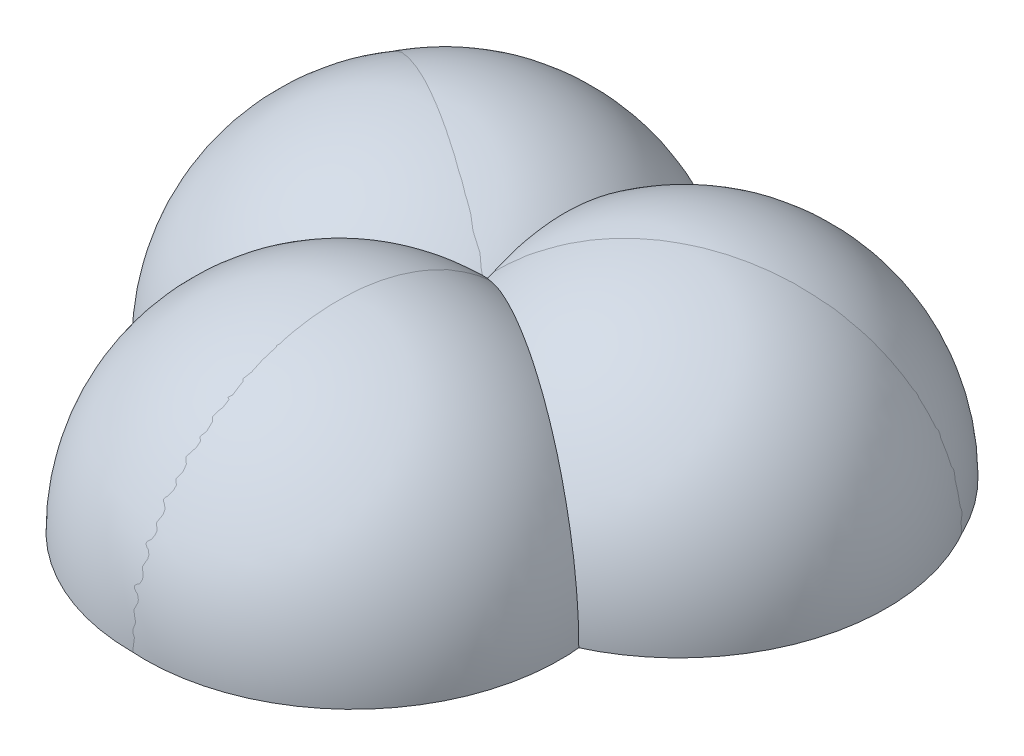
SolidWorks part; units mm, degrees
ref_plane "Front Plane" through (0, 0, 0) normal (0, 0, 1) x (1, 0, 0)
ref_plane "Top Plane" through (0, 0, 0) normal (0, 1, 0) x (1, 0, 0)
ref_plane "Right Plane" through (0, 0, 0) normal (1, 0, 0) x (0, 0, -1)
sketch "bottom sketch template" plane through (0, 0, 0) normal (0, 1, 0) x (1, 0, 0)
  line L0 (-177.6403, 0) -> (177.6403, 0) construction
  line L1 (0, 150.0743) -> (0, -150.0743) construction
  line L2 (-88.9, 150.0743) -> (88.9, 150.0743) construction
  line L3 (88.9, 150.0743) -> (177.6403, 0) construction
  line L4 (177.6403, 0) -> (82.296, -150.0743) construction
  line L5 (82.296, -150.0743) -> (-82.296, -150.0743) construction
  line L6 (-82.296, -150.0743) -> (-177.6403, 0) construction
  line L7 (-177.6403, 0) -> (-88.9, 150.0743) construction
  line L8 (129.9682, -75.0372) -> (0, 0) construction
  line L9 (0, 0) -> (-129.9682, -75.0372) construction
  line L10 (0, 0) -> (136.1081, -65.3728) construction
  line L11 (123.8607, -84.6505) -> (0, 0) construction
  line L12 (0, 0) -> (-124.6685, -85.1867) construction
  line L13 (-135.2398, -64.9412) -> (0, 0) construction
  line L14 (0, 0) -> (-11.4395, 150.5594) construction
  line L15 (11.3791, 149.5917) -> (0, 0) construction
  point P4 (0, 0)
  point P5 (0, 0)
  point P10 (0, 150.0743)
  point P11 (0, -150.0743)
  point P18 (11.3791, 150.0743)
  point P19 (0, 0)
  point P23 (0, 0)
  dimension "D1" = 177.8
  dimension "D2" = 164.592
  dimension "D3" = 30
  dimension "D4" = 4.345
  dimension "D5" = 4.35
  dimension "D6" = 3
ref_plane "4-5 leg planes" through (0, 0, 84.6505) normal (0, 0, 1) x (1, 0, 0)
ref_plane "1-6 leg planes" through (73.449, 0, -42.6173) normal (0.8649, 0, -0.5019) x (-0.5019, 0, -0.8649)
ref_plane "2-3 leg planes" through (-73.6321, 0, -42.3) normal (-0.8671, 0, -0.4981) x (-0.4981, 0, 0.8671)
ref_plane "3-4 leg plane" through (-126.5583, 0, 80.4043) normal (0.8441, 0, -0.5362) x (-0.5362, 0, -0.8441)
ref_plane "1-2 leg plane" through (0, 0, -150.0743) normal (0, 0, -1) x (-1, 0, 0)
ref_plane "5-6 leg plane" through (126.5583, 0, 80.4043) normal (-0.8441, 0, -0.5362) x (-0.5362, 0, 0.8441)
sketch "leg 1 center sketch" plane through (0, 0, 0) normal (0, 1, 0) x (1, 0, 0)
  line L0 (11.4159, 150.0743) -> (-106.5772, 68.3873) construction
  line L1 (-177.6403, 0) -> (177.6403, 0) construction
  line L2 (-88.9, 150.0743) -> (88.9, 150.0743) construction
  line L3 (11.3791, 149.5917) -> (0, 0) construction
  point P5 (-55.1177, 133.0637)
  point P6 (0, 0)
  dimension "D1" = 143.51
  dimension "D2" = 34.695
sketch "Sketch9" plane through (0, 0, 0) normal (0, 1, 0) x (1, 0, 0)
  line L0 (-106.5772, 68.3873) -> (-106.5772, 188.3769) construction
  line L1 (-106.5772, 188.3769) -> (-106.5772, 253.6803)
  line L2 (-106.5772, 68.3873) -> (-106.5772, -51.6023) construction
  line L3 (-106.5772, -51.6023) -> (-106.5772, -116.9057)
  arc A0 (-106.5772, -51.6023) -> (-106.5772, 188.3769) centre (-106.5772, 68.3873) ccw
  arc A1 (-106.5772, -116.9057) -> (-106.5772, 253.6803) centre (-106.5772, 68.3873) ccw
  dimension "D1" = 239.9792
  dimension "D2" = 370.586
revolve "leg 1 revolve" add sketch "Sketch9" angle 180 about L0
sketch "leg 2 center sketch" plane through (0, 0, 0) normal (0, 1, 0) x (1, 0, 0)
  line L0 (-11.4395, 150.5594) -> (106.5463, 68.8621) construction
  line L1 (11.4159, 150.0743) -> (-106.5772, 68.3873) construction
  line L2 (-177.6403, 0) -> (177.6403, 0) construction
  dimension "D1" = 34.7
sketch "Sketch11" plane through (0, 0, 0) normal (0, 1, 0) x (1, 0, 0)
  line L0 (106.5463, 68.8621) -> (106.5463, 188.8517) construction
  line L1 (106.5463, 188.8517) -> (106.5463, 254.1551)
  line L2 (106.5463, 68.8621) -> (106.5463, -51.1275) construction
  line L3 (106.5463, -51.1275) -> (106.5463, -116.4309)
  arc A0 (106.5463, -51.1275) -> (106.5463, 188.8517) centre (106.5463, 68.8621) ccw
  arc A1 (106.5463, -116.4309) -> (106.5463, 254.1551) centre (106.5463, 68.8621) ccw
  point P5 (136.8729, 142.0015)
  point P6 (0, 0)
  dimension "D1" = 119.9896
  dimension "D2" = 185.293
revolve "leg 2 revolve" add sketch "Sketch11" angle 180 about L0
sketch "Sketch14" plane through (0, 0, 0) normal (0, 1, 0) x (1, 0, 0)
  line L0 (-135.2398, -64.9412) -> (-5.5003, -126.2827) construction
  line L1 (11.4159, 150.0743) -> (-106.5772, 68.3873) construction
  line L2 (82.296, -150.0743) -> (-82.296, -150.0743) construction
  line L3 (-5.5003, -126.2827) -> (-5.5003, -6.2931) construction
  line L4 (-5.5003, -6.2931) -> (-5.5003, 59.0103)
  line L5 (-5.5003, -126.2827) -> (-5.5003, -246.2723) construction
  line L6 (-5.5003, -246.2723) -> (-5.5003, -311.5757)
  arc A0 (-5.5003, -246.2723) -> (-5.5003, -6.2931) centre (-5.5003, -126.2827) ccw
  arc A1 (-5.5003, -311.5757) -> (-5.5003, 59.0103) centre (-5.5003, -126.2827) ccw
  point P12 (-5.5003, -131.5546)
  dimension "D2" = 119.9896
  dimension "D3" = 185.293
  dimension "D1" = 25.305
revolve "leg 3 revolve" add sketch "Sketch14" angle 180 about L3
sketch "Sketch15" plane through (0, 0, 0) normal (0, 1, 0) x (1, 0, 0)
  line L0 (-124.6685, -85.1867) -> (-112.9095, 57.8408) construction
  line L1 (11.4159, 150.0743) -> (-106.5772, 68.3873) construction
  line L2 (-177.6403, 0) -> (177.6403, 0) construction
  line L3 (-112.9095, 57.8408) -> (-112.9095, 177.8304) construction
  line L4 (-112.9095, 177.8304) -> (-112.9095, 243.1338)
  line L5 (-112.9095, 57.8408) -> (-112.9095, -62.1488) construction
  line L6 (-112.9095, -62.1488) -> (-112.9095, -127.4522)
  arc A0 (-112.9095, -62.1488) -> (-112.9095, 177.8304) centre (-112.9095, 57.8408) ccw
  arc A1 (-112.9095, -127.4522) -> (-112.9095, 243.1338) centre (-112.9095, 57.8408) ccw
  point P12 (-109.0599, 57.8408)
  dimension "D2" = 119.9896
  dimension "D3" = 185.293
  dimension "D1" = 85.3
revolve "leg 4 revolve" add sketch "Sketch15" angle 180 about L3
sketch "Sketch16" plane through (0, 0, 0) normal (0, 1, 0) x (1, 0, 0)
  line L0 (123.8607, -84.6505) -> (112.1017, 58.3769) construction
  line L1 (11.4159, 150.0743) -> (-106.5772, 68.3873) construction
  line L2 (-177.6403, 0) -> (177.6403, 0) construction
  line L3 (112.1017, 58.3769) -> (112.1017, 178.3665) construction
  line L4 (112.1017, 178.3665) -> (112.1017, 243.6699)
  line L5 (112.1017, 58.3769) -> (112.1017, -61.6127) construction
  line L6 (112.1017, -61.6127) -> (112.1017, -126.9161)
  arc A0 (112.1017, -61.6127) -> (112.1017, 178.3665) centre (112.1017, 58.3769) ccw
  arc A1 (112.1017, -126.9161) -> (112.1017, 243.6699) centre (112.1017, 58.3769) ccw
  point P12 (116.4209, 54.9312)
  dimension "D2" = 119.9896
  dimension "D3" = 185.293
  dimension "D1" = 85.3
revolve "leg 5 revolve" add sketch "Sketch16" angle 180 about L3
sketch "Sketch12" plane through (0, 0, 0) normal (0, 1, 0) x (1, 0, 0)
  line L0 (136.1081, -65.3728) -> (6.3685, -126.7142) construction
  line L1 (11.4159, 150.0743) -> (-106.5772, 68.3873) construction
  line L2 (82.296, -150.0743) -> (-82.296, -150.0743) construction
  line L3 (6.3685, -126.7142) -> (6.3685, -6.7246) construction
  line L4 (6.3685, -6.7246) -> (6.3685, 58.5788)
  line L5 (6.3685, -126.7142) -> (6.3685, -246.7038) construction
  line L6 (6.3685, -246.7038) -> (6.3685, -312.0072)
  arc A0 (6.3685, -246.7038) -> (6.3685, -6.7246) centre (6.3685, -126.7142) ccw
  arc A1 (6.3685, -312.0072) -> (6.3685, 58.5788) centre (6.3685, -126.7142) ccw
  point P12 (6.3685, -131.0686)
  dimension "D2" = 119.9896
  dimension "D3" = 185.293
  dimension "D1" = 25.305
revolve "leg 6 revolve" add sketch "Sketch12" angle 180 about L3
